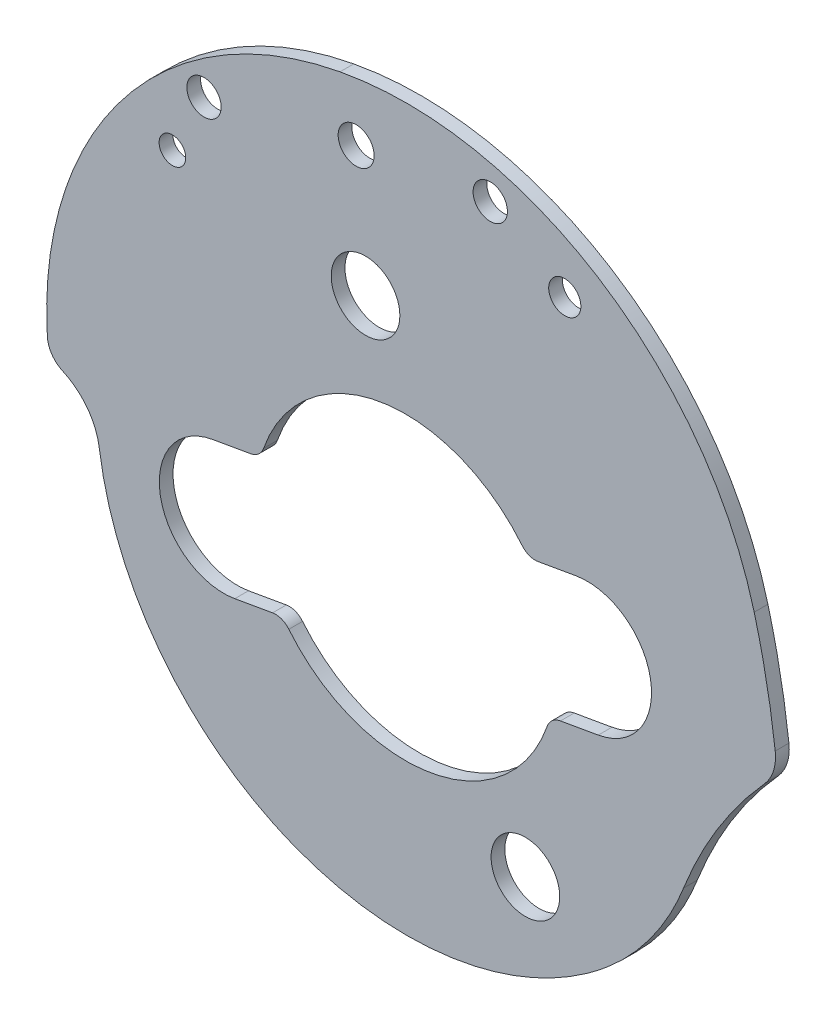
SolidWorks part; units mm, degrees
ref_plane "Front Plane" through (0, 0, 0) normal (0, 0, 1) x (1, 0, 0)
ref_plane "Top Plane" through (0, 0, 0) normal (0, 1, 0) x (1, 0, 0)
ref_plane "Right Plane" through (0, 0, 0) normal (1, 0, 0) x (0, 0, -1)
sketch "Model" plane through (0, 0, 0) normal (0, 0, 1) x (1, 0, 0)
  ellipse E0 centre (17.3961, -51.3806) end of major axis (24.377, -51.3806) minor radius 6.9809
  ellipse E1 centre (-16.1629, -32.5692) end of major axis (-16.1629, -22.9191) minor radius 9.6501
  ellipse E2 centre (22.9927, -25.7173) end of major axis (32.2627, -25.7173) minor radius 9.27
  ellipse E3 centre (-20.0573, 8.5758) end of major axis (-20.0573, 11.4811) minor radius 2.9053
  ellipse E4 centre (-23.8725, 1.541) end of major axis (-27.1922, 1.541) minor radius 3.3197
  ellipse E5 centre (-2.4343, 12.5766) end of major axis (-2.4343, 17.9393) minor radius 5.3627
  ellipse E6 centre (13.2993, 14.7207) end of major axis (13.2993, 18.4351) minor radius 3.7144
  ellipse E7 centre (-1.2327, -2.0433) end of major axis (-1.2327, 3.1634) minor radius 5.2067
  ellipse E8 centre (22.0604, 9.5702) end of major axis (22.0604, 13.1612) minor radius 3.591
  spline S0 degree 3 poles (44.0581, -11.3354) (38.4033, 9.8661) (17.3587, 23.1222) (-4.2058, 19.0663) knots 0 0 0 0 0.333333 0.333333 0.333333 0.333333
  spline S1 degree 3 poles (-4.2058, 19.0663) (-25.7703, 15.0105) (-40.5609, -4.9853) (-38.1268, -26.7925) knots 0.333333 0.333333 0.333333 0.333333 1 1 1 1
  spline S2 degree 3 poles (46.7562, -26.4745) (46.284, -21.3612) (45.3815, -16.2969) (44.0581, -11.3354) knots 0 0 0 0 1 1 1 1
  spline S3 degree 3 poles (46.7562, -26.4745) (42.0043, -31.2778) (38.2846, -37.0019) (35.8253, -43.295) knots 0 0 0 0 1 1 1 1
  spline S4 degree 3 poles (26.8478, -55.776) (30.8425, -52.4371) (33.9303, -48.1443) (35.8253, -43.295) knots 0 0 0 0 1 1 1 1
  spline S5 degree 3 poles (-32.2525, -32.9684) (-30.442, -46.0069) (-21.6996, -57.0365) (-9.4187, -61.7758) knots 0 0 0 0 0.333333 0.333333 0.333333 0.333333
  spline S6 degree 3 poles (-9.4187, -61.7758) (2.8622, -66.5152) (16.7476, -64.218) (26.8478, -55.776) knots 0.333333 0.333333 0.333333 0.333333 1 1 1 1
  spline S7 degree 3 poles (-32.2525, -32.9684) (-32.6837, -29.8631) (-35.047, -27.3785) (-38.1268, -26.7925) knots 0 0 0 0 1 1 1 1
extrude "Boss-Extrude1" add sketch "Model" along normal blind 1.6 contours S0 S1 S7 S5 S6 S4 S3 S2
sketch "Sketch2" plane through (0, 0, 1.6) normal (0, 0, 1) x (1, 0, 0)
  line L0 (-16.1629, -32.5692) -> (22.9927, -25.7173) construction
  line L1 (-16.1629, -32.5692) -> (-44.755, -37.5726) construction
  line L2 (22.9927, -25.7173) -> (60.316, -19.186) construction
  line L3 (-19.0561, -25.4615) -> (-14.6524, -24.6909)
  line L4 (-16.4705, -40.237) -> (-12.0668, -39.4664)
  line L5 (18.8966, -18.8201) -> (23.3003, -18.0495)
  line L6 (21.4822, -33.5956) -> (25.8859, -32.825)
  circle A0 centre (17.3961, -51.3806) radius 4
  circle A1 centre (-1.2327, -2.0433) radius 4
  arc A2 (16.9993, -18.1109) -> (-13.1087, -23.3795) centre (3.4149, -29.1432) ccw
  arc A3 (-19.0561, -25.4615) -> (-16.4705, -40.237) centre (-17.7633, -32.8493) ccw
  arc A4 (21.4822, -33.5956) -> (19.9385, -34.907) centre (21.8269, -35.5657) ccw
  arc A5 (-10.1695, -40.1756) -> (19.9385, -34.907) centre (3.4149, -29.1432) ccw
  arc A6 (25.8859, -32.825) -> (23.3003, -18.0495) centre (24.5931, -25.4372) ccw
  arc A7 (16.9993, -18.1109) -> (18.8966, -18.8201) centre (18.5519, -16.8501) ccw
  arc A8 (-10.1695, -40.1756) -> (-12.0668, -39.4664) centre (-11.7221, -41.4364) ccw
  arc A9 (-14.6524, -24.6909) -> (-13.1087, -23.3795) centre (-14.9971, -22.7208) ccw
  circle A10 centre (-20.0573, 8.5758) radius 2
  circle A11 centre (13.2993, 14.7207) radius 2
  circle A12 centre (-23.7377, 1.389) radius 1.5512
  circle A13 centre (-2.3283, 12.5764) radius 2.0969
  circle A14 centre (21.9843, 9.4206) radius 1.8743
  point P27 (17.6968, -19.0301)
  dimension "D1" = 8
  dimension "D2" = 8
  dimension "D3" = 35
  dimension "D4" = 2
  dimension "D5" = 15
  dimension "D6" = 4
  dimension "D7" = 4
extrude "Cut-Extrude1" cut sketch "Sketch2" against normal blind 1.6
fillet "Fillet1" radius 3 1 edges at (-38.1268, -26.7925, 0.8)
fillet "Fillet2" radius 5 1 edges at (46.7562, -26.4745, 0.8)
